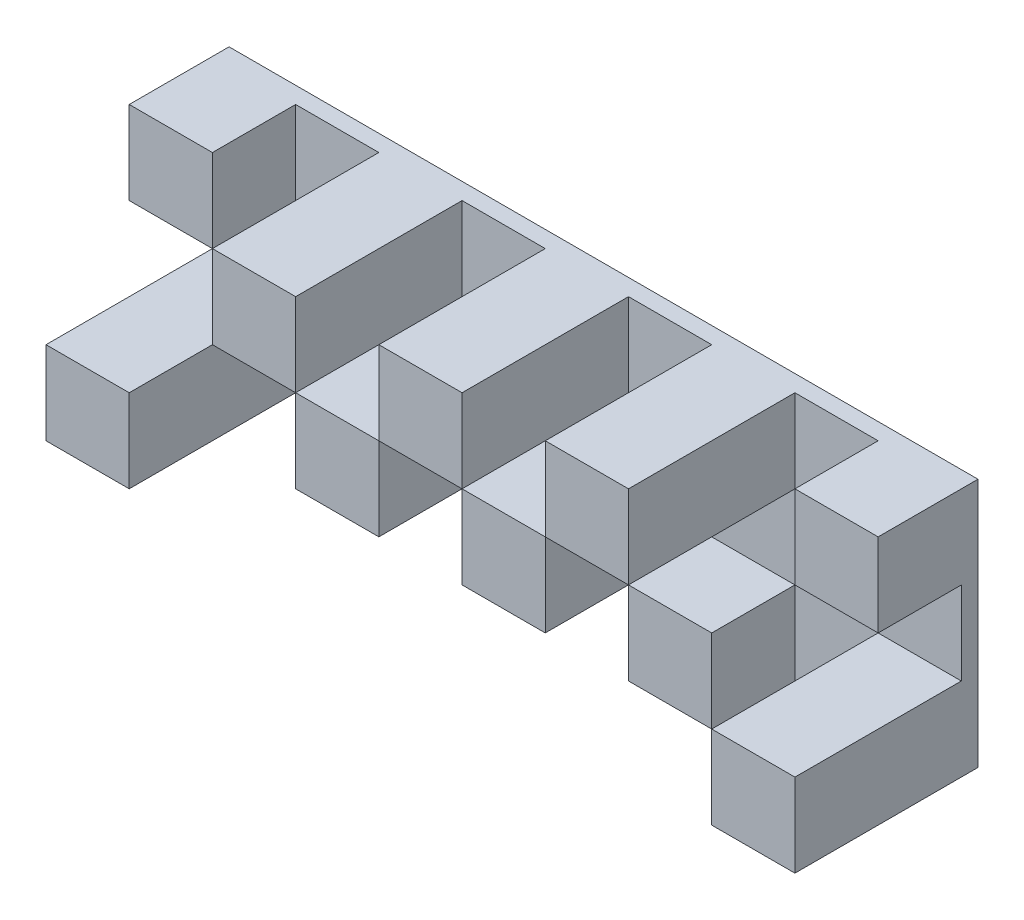
SolidWorks part; units mm, degrees
ref_plane "Front Plane" through (0, 0, 0) normal (0, 0, 1) x (1, 0, 0)
ref_plane "Top Plane" through (0, 0, 0) normal (0, 1, 0) x (1, 0, 0)
ref_plane "Right Plane" through (0, 0, 0) normal (1, 0, 0) x (0, 0, -1)
sketch "Sketch1" plane through (0, 0, 0) normal (0, 1, 0) x (1, 0, 0)
  point P5 (0, 0)
  point P6 (0, 0)
  point P7 (0, 0)
  point P112 (0, 0)
  point P113 (0, 0)
sketch "Sketch2" plane through (0, 0, 0) normal (0, 0, 1) x (1, 0, 0)
  line L1 (0, 0) -> (450000, 0)
  line L2 (0, 0) -> (0, 150000)
  line L3 (0, 150000) -> (450000, 150000)
  line L4 (450000, 0) -> (450000, 150000)
  point P4 (0, 0)
  point P9 (0, 0)
  point P10 (0, 0)
  point P47 (0, 0)
  point P48 (0, 0)
  dimension "D1" = 150000
  dimension "D2" = 450000
extrude "Boss-Extrude2" add sketch "Sketch2" along normal blind 10000 contours L2 L1 L4 L3
sketch "Sketch4" plane through (0, 0, 10000) normal (0, 0, 1) x (1, 0, 0)
  line L0 (400000, 0) -> (450000, 0)
  line L1 (0, 0) -> (50000, 0)
  line L2 (0, 0) -> (0, 50000)
  line L3 (0, 50000) -> (50000, 50000)
  line L4 (50000, 0) -> (50000, 50000)
  line L5 (400000, 0) -> (400000, 50000)
  line L6 (400000, 50000) -> (450000, 50000)
  line L7 (450000, 0) -> (450000, 50000)
  line L8 (300000, 100000) -> (350000, 100000)
  line L9 (300000, 100000) -> (300000, 150000)
  line L10 (300000, 150000) -> (350000, 150000)
  line L11 (350000, 100000) -> (350000, 150000)
  line L12 (0, 150000) -> (450000, 150000) construction
  line L13 (200000, 100000) -> (250000, 100000)
  line L14 (250000, 100000) -> (250000, 150000)
  line L15 (200000, 150000) -> (250000, 150000)
  line L16 (200000, 100000) -> (200000, 150000)
  line L17 (100000, 100000) -> (150000, 100000)
  line L18 (150000, 100000) -> (150000, 150000)
  line L19 (100000, 150000) -> (150000, 150000)
  line L20 (100000, 100000) -> (100000, 150000)
  point P9 (0, 0)
  line M21 (450000, 150000) -> (0, 150000)
  line M22 (0, 150000) -> (0, 0)
  line M23 (0, 0) -> (450000, 0)
  line M24 (450000, 0) -> (450000, 150000)
  dimension "D1" = 50000
  dimension "D2" = 100000
  dimension "D3" = 3
  dimension "D4" = 50000
extrude "Boss-Extrude5" add sketch "Sketch4" along normal blind 100000 contours L16 L13 L14 M21 | L8 L11 L9 M21 | L6 L5 M23 M24 | L4 L3 M23 M22 | L17 L18 L19 L20
sketch "Sketch5" plane through (0, 0, 10000) normal (0, 0, 1) x (1, 0, 0)
  line L0 (0, 100000) -> (50000, 100000)
  line L1 (0, 100000) -> (0, 150000)
  line L2 (0, 150000) -> (50000, 150000)
  line L3 (50000, 100000) -> (50000, 150000)
  line L4 (400000, 100000) -> (450000, 100000)
  line L5 (400000, 100000) -> (400000, 150000)
  line L6 (400000, 150000) -> (450000, 150000)
  line L7 (450000, 100000) -> (450000, 150000)
  line L8 (100000, 0) -> (150000, 0)
  line L9 (100000, 0) -> (100000, 50000)
  line L10 (100000, 50000) -> (150000, 50000)
  line L11 (150000, 0) -> (150000, 50000)
  line L12 (50000, 0) -> (400000, 0) construction
  line L13 (200000, 0) -> (250000, 0)
  line L14 (250000, 0) -> (250000, 50000)
  line L15 (200000, 50000) -> (250000, 50000)
  line L16 (200000, 0) -> (200000, 50000)
  line L17 (300000, 0) -> (350000, 0)
  line L18 (350000, 0) -> (350000, 50000)
  line L19 (300000, 50000) -> (350000, 50000)
  line L20 (300000, 0) -> (300000, 50000)
  line M22 (100000, 150000) -> (0, 150000)
  line M23 (0, 150000) -> (0, 50000)
  line M26 (50000, 0) -> (400000, 0)
  dimension "D1" = 50000
  dimension "D2" = 50000
  dimension "D3" = 3
extrude "Boss-Extrude6" add sketch "Sketch5" along normal blind 50000 contours L20 L18 L19 M26 | L16 L14 L15 M26 | L11 L10 L9 M26 | L0 L3 M22 M23 | L4 L7 L6 L5
